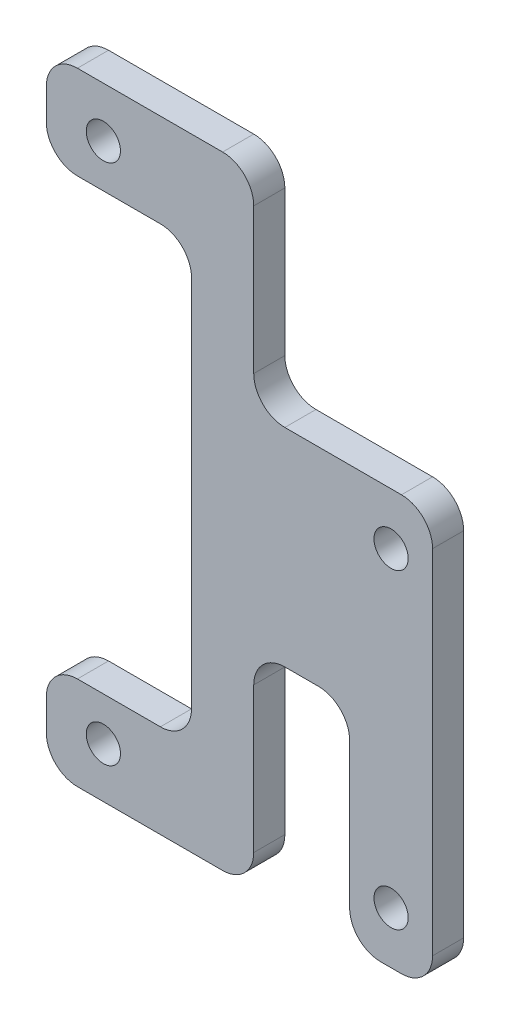
SolidWorks part; units mm, degrees
ref_plane "Front Plane" through (0, 0, 0) normal (0, 0, 1) x (1, 0, 0)
ref_plane "Top Plane" through (0, 0, 0) normal (0, 1, 0) x (1, 0, 0)
ref_plane "Right Plane" through (0, 0, 0) normal (1, 0, 0) x (0, 0, -1)
sketch "Sketch1" plane through (0, 0, 0) normal (0, 0, 1) x (1, 0, 0)
  line L8 (-35.3845, 0) -> (43.3618, 0) construction
  line L9 (-4, 20) -> (4, 20)
  line L10 (-4, 20) -> (-4, -20)
  line L11 (-4, -20) -> (4, -20)
  line L12 (4, 20) -> (4, -20)
  line L13 (-4, 20) -> (4, -20) construction
  line L14 (-4, -20) -> (4, 20) construction
  line L15 (0, 28.0694) -> (0, -29.0843) construction
  line L16 (-22.9881, 15) -> (22.2389, 15) construction
  line L17 (-22.9881, -15) -> (22.2389, -15) construction
  circle A3 centre (0, 15) radius 1.65
  circle A4 centre (0, -15) radius 1.65
  point P0 (0, 0)
  dimension "D1" = 40
  dimension "D2" = 8
  dimension "D4" = 3.3
  dimension "D3" = 30
extrude "Boss-Extrude1" add sketch "Sketch1" along normal blind 3
sketch "Sketch9" plane through (-4, 0, 0) normal (-1, 0, 0) x (0, 0, 1)
  line L0 (3, 20) -> (3, -20) construction
  line L1 (0, 20) -> (3, 20)
  line L2 (0, 20) -> (0, 0)
  line L3 (0, 0) -> (3, 0)
  line L4 (3, 20) -> (3, 0)
  dimension "D1" = 20
extrude "Boss-Extrude6" add sketch "Sketch9" along normal blind 9.245
sketch "Sketch10" plane through (-13.245, 0, 0) normal (-1, 0, 0) x (0, 0, 1)
  line L0 (-11.483, 10) -> (15.7939, 10) construction
  line L1 (1.5, 29.6966) -> (1.5, -10.5911) construction
  line L2 (3, 0) -> (3, -20) construction
  line L3 (0, 40) -> (3, 40)
  line L4 (0, 40) -> (0, -20)
  line L5 (0, -20) -> (3, -20)
  line L6 (3, 40) -> (3, -20)
  line L7 (0, 40) -> (3, -20) construction
  line L8 (0, -20) -> (3, 40) construction
  line L9 (3, 20) -> (0, 20) construction
  point P4 (1.5, 10)
  dimension "D1" = 60
  dimension "D2" = 10
extrude "Boss-Extrude7" add sketch "Sketch10" along normal blind 20
sketch "Sketch11" plane through (0, 0, 3) normal (0, 0, 1) x (1, 0, 0)
  line L0 (-43.3748, 10) -> (16.6147, 10) construction
  line L2 (-33.245, -20) -> (-33.245, 40) construction
  line L3 (-33.245, 31) -> (-19.245, 31)
  line L4 (-19.245, 31) -> (-19.245, -11)
  line L5 (-33.245, -11) -> (-19.245, -11)
  line L6 (-33.245, 31) -> (-33.245, -11)
  line L7 (-33.245, 40) -> (-13.245, 40) construction
  point P9 (-19.245, 10)
  dimension "D1" = 9
  dimension "D2" = 30
  dimension "D3" = 14
extrude "Cut-Extrude1" cut sketch "Sketch11" against normal blind 10
sketch "Sketch12" plane through (0, 0, 3) normal (0, 0, 1) x (1, 0, 0)
  line L0 (-39.8323, 35.17) -> (-1.7572, 35.17) construction
  line L1 (-50.954, 10) -> (15.1746, 10) construction
  line L2 (-27.745, 59.7378) -> (-27.745, 32.8332) construction
  line L3 (-33.245, 31) -> (-33.245, 40) construction
  line L4 (-27.745, -39.7378) -> (-27.745, -12.8332) construction
  line L5 (-39.8323, -15.17) -> (-1.7572, -15.17) construction
  line L8 (-19.245, 31) -> (-33.245, 31) construction
  circle A0 centre (-27.745, 35.17) radius 1.65
  circle A1 centre (-27.745, -15.17) radius 1.65
  dimension "D2" = 25.17
  dimension "D4" = 3.3
  dimension "D1" = 5.5
  dimension "D3" = 21
extrude "Cut-Extrude2" cut sketch "Sketch12" against normal blind 10
fillet "Fillet7" radius 3 14 edges at (4, -20, 1.5) (-4, -20, 1.5) (-4, 0, 1.5) (-13.245, 0, 1.5) (-13.245, -20, 1.5) (-33.245, -20, 1.5) (-33.245, -11, 1.5) (-19.245, -11, 1.5) (4, 20, 1.5) (-13.245, 20, 1.5) (-13.245, 40, 1.5) (-19.245, 31, 1.5) (-33.245, 31, 1.5) (-33.245, 40, 1.5)
